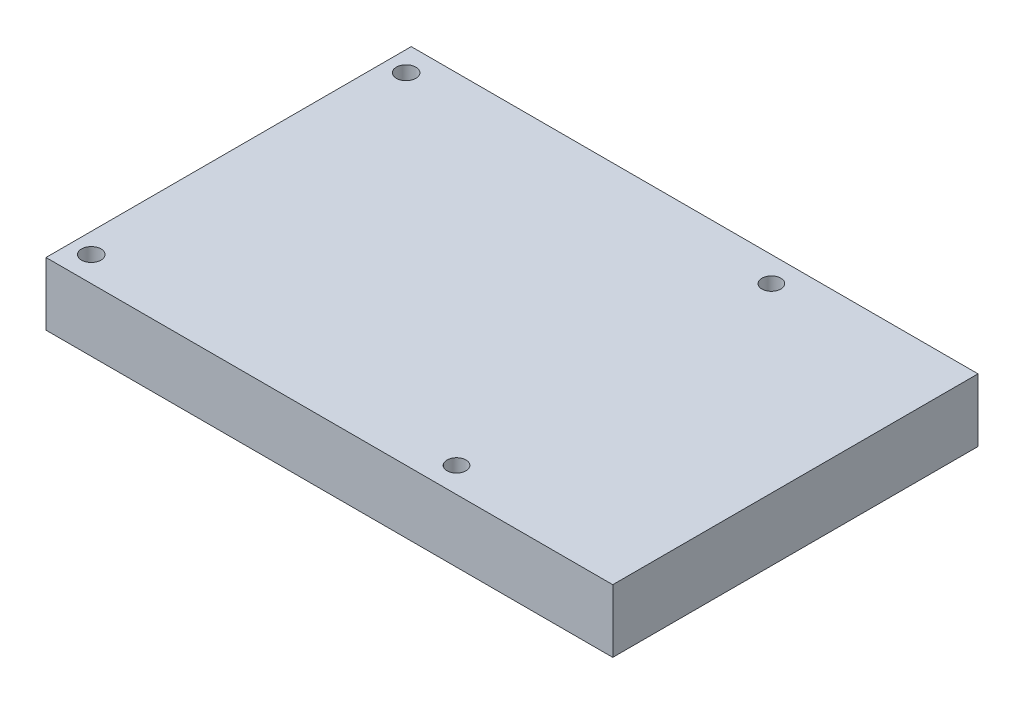
SolidWorks part; units mm, degrees
ref_plane "前视基准面" through (0, 0, 0) normal (0, 0, 1) x (1, 0, 0)
ref_plane "上视基准面" through (0, 0, 0) normal (0, 1, 0) x (1, 0, 0)
ref_plane "右视基准面" through (0, 0, 0) normal (1, 0, 0) x (0, 0, -1)
sketch "草图1" plane through (0, 0, 0) normal (0, 1, 0) x (1, 0, 0)
  line L1 (-45, -29) -> (45, -29)
  line L2 (-45, -29) -> (-45, 29)
  line L3 (-45, 29) -> (45, 29)
  line L4 (45, -29) -> (45, 29)
  line L5 (-45, -29) -> (45, 29) construction
  line L6 (-45, 29) -> (45, -29) construction
  point P0 (0, 0)
  dimension "D1" = 58
  dimension "D2" = 90
extrude "凸台-拉伸1" add sketch "草图1" along normal blind 10
sketch "草图2" plane through (0, 10, 0) normal (0, 1, 0) x (1, 0, 0)
  line L0 (-50.6053, 0) -> (47.8566, 0) construction
  line L1 (0, 33.8692) -> (0, -36.1292) construction
  circle A0 centre (-41.8097, 25) radius 1.55
  circle A1 centre (16.1903, 25) radius 1.5
  circle A2 centre (-41.8097, -25) radius 1.55
  circle A3 centre (16.1903, -25) radius 1.5
  dimension "D1" = 3.1
  dimension "D2" = 50
  dimension "D3" = 3
  dimension "D4" = 58
extrude "切除-拉伸1" cut sketch "草图2" against normal blind 10
